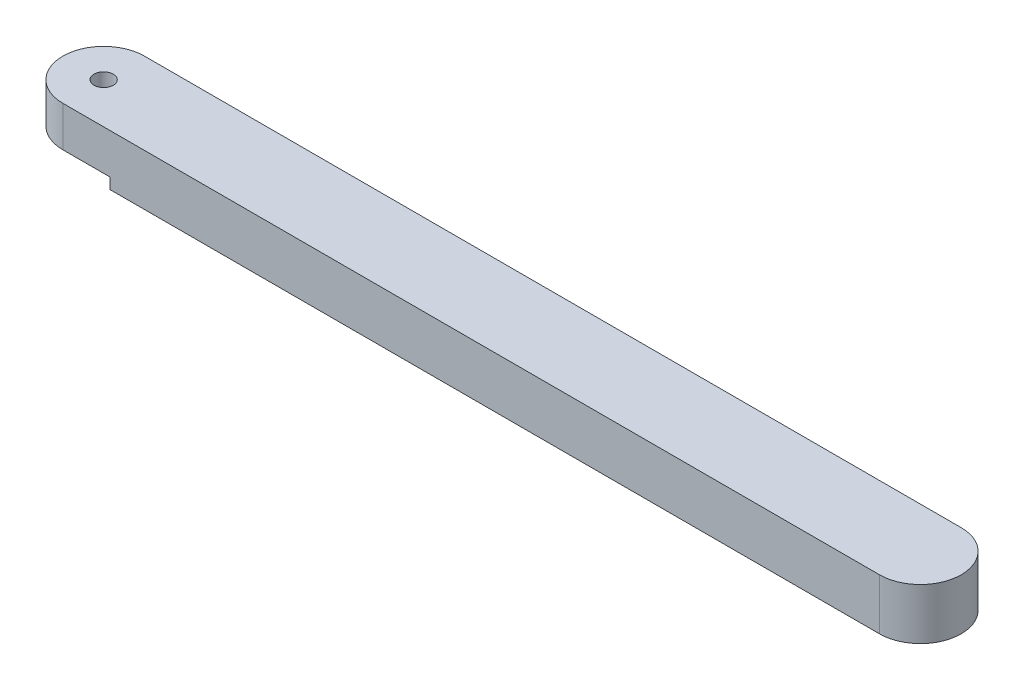
SolidWorks part; units mm, degrees
ref_plane "Front Plane" through (0, 0, 0) normal (0, 0, 1) x (1, 0, 0)
ref_plane "Top Plane" through (0, 0, 0) normal (0, 1, 0) x (1, 0, 0)
ref_plane "Right Plane" through (0, 0, 0) normal (1, 0, 0) x (0, 0, -1)
sketch "Sketch1" plane through (0, 0, 0) normal (0, 1, 0) x (1, 0, 0)
  line L0 (0, 0) -> (190.5, 0) construction
  line L1 (0, 9.525) -> (190.5, 9.525)
  line L2 (0, -9.525) -> (190.5, -9.525)
  arc A0 (0, 9.525) -> (0, -9.525) centre (0, 0) ccw
  arc A1 (190.5, -9.525) -> (190.5, 9.525) centre (190.5, 0) ccw
  point P2 (95.25, 0)
  dimension "D2" = 19.05
  dimension "D1" = 190.5
extrude "Boss-Extrude1" add sketch "Sketch1" along normal blind 11.938
hole_wizard "Ø4.5 (4.5) Diameter Hole1" positions "Sketch2" profile "Sketch3" hole size "Ø4.5" standard "ANSI Metric" end condition up to next
sketch "Sketch2" plane through (0, 11.938, 0) normal (0, 1, 0) x (1, 0, 0)
  point P0 (0, 0)
sketch "Sketch3" plane through (0, 11.938, 0) normal (1, 0, 0) x (0, 0, 1)
  line L0 (0, 0) -> (0, 11.938)
  line L1 (0, 11.938) -> (2.25, 11.938)
  line L2 (2.25, 11.938) -> (2.25, 0)
  line L5 (2.25, 0) -> (0, 0)
  line L11 (0, -6.35) -> (0, 107.95) construction
  dimension "Thru Hole Dia." = 4.5
  dimension "Thru Hole Depth" = 11.938
sketch "Sketch5" plane through (0, 0, 0) normal (0, -1, 0) x (1, 0, 0)
  line L1 (10.9727, 9.525) -> (0, 9.525)
  line L3 (10.9727, -9.525) -> (0, -9.525)
  line L5 (0, 9.525) -> (190.5, 9.525) construction
  line L8 (190.5, -9.525) -> (0, -9.525) construction
  line L9 (11.9341, 4.3437) -> (10.9727, 6.985)
  line L10 (10.9727, 6.985) -> (10.9727, 9.525)
  line L11 (11.9341, -4.3437) -> (10.9727, -6.985)
  line L12 (10.9727, -6.985) -> (10.9727, -9.525)
  arc A0 (0, 9.525) -> (0, -9.525) centre (0, 0) ccw
  arc A1 (0, 9.525) -> (0, -9.525) centre (0, 0) ccw construction
  arc A2 (11.9341, -4.3437) -> (11.9341, 4.3437) centre (0, 0) ccw
  dimension "D1" = 12.7
  dimension "D2" = 40
  dimension "D3" = 2.54
extrude "Cut-Extrude1" cut sketch "Sketch5" against normal blind 2.54
